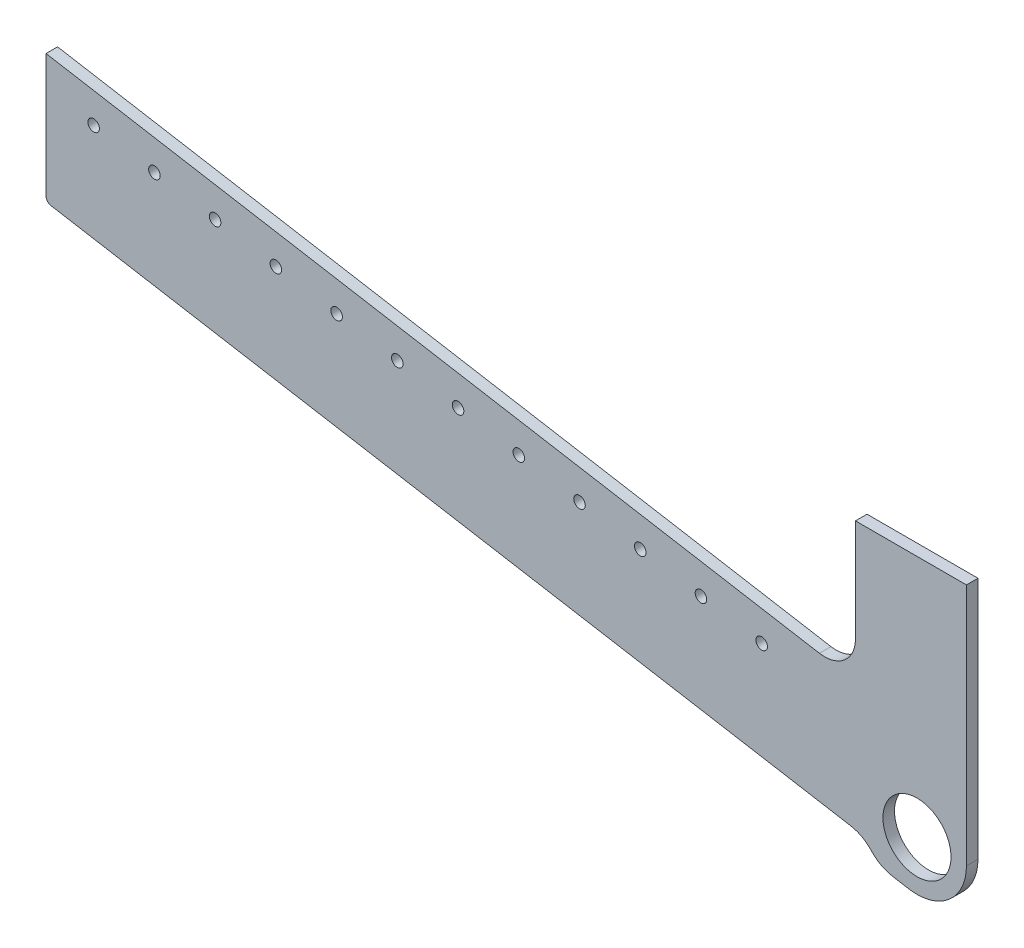
SolidWorks part; units mm, degrees
material "Polypropylene"
ref_plane "Front Plane" through (0, 0, 0) normal (0, 0, 1) x (1, 0, 0)
ref_plane "Top Plane" through (0, 0, 0) normal (0, 1, 0) x (1, 0, 0)
ref_plane "Right Plane" through (0, 0, 0) normal (1, 0, 0) x (0, 0, -1)
sketch "Sketch1" plane through (0, 0, 0) normal (0, 0, 1) x (1, 0, 0)
  line L0 (19.05, 0) -> (19.05, -76.2) construction
  line L1 (0, 19.05) -> (-57.15, 19.05) construction
  line L2 (19.05, -155.575) -> (168.9894, -155.575) construction
  line L3 (0, -95.25) -> (-57.15, -95.25) construction
  line L4 (-57.15, -95.25) -> (-57.15, 19.05) construction
  line L5 (168.9894, 7.239) -> (168.9894, -18.161) construction
  line L6 (168.9894, -18.161) -> (168.9894, -155.575) construction
  line L7 (168.9894, 7.239) -> (143.6189, 6.0141) construction
  line L8 (143.6189, 6.0141) -> (19.05, 0) construction
  line L9 (165.5424, -12.8509) -> (158.8645, -11.7052)
  line L12 (197.5644, 110.4886) -> (197.5644, -33.1911) construction
  line L16 (-190.0553, 107.5461) -> (-190.0553, 56.7461)
  line L17 (-190.0553, 107.5461) -> (128.7712, 52.8423)
  line L23 (-187.9448, 54.2427) -> (141.5847, -2.2975)
  line L24 (143.6189, 65.3594) -> (143.6189, 107.5461)
  line L25 (143.6189, 107.5461) -> (189.3729, 107.5461)
  line L50 (189.3729, 107.5461) -> (189.3729, 7.239)
  arc A0 (19.05, 0) -> (0, 19.05) centre (0, 0) ccw construction
  arc A1 (19.05, -76.2) -> (0, -95.25) centre (0, -76.2) cw construction
  circle A2 centre (168.9894, 7.239) radius 14.0335
  arc A3 (168.9894, -18.161) -> (143.6189, 6.0141) centre (168.9894, 7.239) ccw construction
  arc A4 (165.5424, -12.8509) -> (189.3729, 7.239) centre (168.9894, 7.239) ccw
  circle A15 centre (104.9708, 44.4781) radius 2.3812
  circle A16 centre (79.9366, 48.7734) radius 2.3813
  circle A17 centre (54.9024, 53.0687) radius 2.3812
  circle A18 centre (29.8682, 57.3641) radius 2.3812
  circle A19 centre (4.8341, 61.6594) radius 2.3813
  circle A20 centre (-20.2001, 65.9547) radius 2.3813
  circle A21 centre (-45.2343, 70.2501) radius 2.3813
  circle A22 centre (-70.2685, 74.5454) radius 2.3813
  arc A31 (-187.9448, 54.2427) -> (-190.0553, 56.7461) centre (-187.5153, 56.7461) cw
  arc A34 (158.8645, -11.7052) -> (150.2246, -7.0013) centre (161.4417, 3.3154) cw
  arc A48 (141.5847, -2.2975) -> (150.2246, -7.0013) centre (139.0075, -17.318) cw
  arc A101 (128.7712, 52.8423) -> (143.6189, 65.3594) centre (130.9189, 65.3594) ccw
  circle A102 centre (-170.4052, 91.7267) radius 2.3812
  circle A103 centre (-145.371, 87.4314) radius 2.3812
  circle A104 centre (-120.3368, 83.1361) radius 2.3813
  circle A105 centre (-95.3027, 78.8407) radius 2.3812
  point P51 (-190.0553, 48.162)
  point P92 (143.8191, 3.8303)
  point P95 (150.6057, -10.2881)
  point P107 (-190.0576, 105.312)
  dimension "D1" = 19.05
  dimension "D4" = 19.05
  dimension "D6" = 28.067
  dimension "D7" = 50.8
  dimension "D10" = 6.35
  dimension "D13" = 28.575
  dimension "D26" = 2.54
  dimension "D27" = 15.24
  dimension "D14" = 12.7
  dimension "D2" = 155.575
  dimension "D3" = 76.2
  dimension "D5" = 114.3
  dimension "D8" = 137.414
  dimension "D9" = 124.714
  dimension "D11" = 12.5
  dimension "D12" = 50.8
  dimension "D40" = 17.2798
  dimension "D41" = 9.4076
extrude "Boss-Extrude1" add sketch "Sketch1" along normal blind 4.7625
sketch "Sketch2" plane through (0, 0, 4.7625) normal (0, 0, 1) x (1, 0, 0)
  line L0 (-188.8163, 48.0139) -> (-189.0331, 50.6154)
  line L1 (-189.2853, 50.8905) -> (-190.3098, 51.0663)
  line L2 (-190.6393, 50.891) -> (-191.7109, 48.5105)
  line L3 (-191.7701, 48.4563) -> (-191.7658, 48.4813) construction
  line L4 (-189.7976, 50.9784) -> (-190.2743, 48.1996) construction
  line L5 (-188.7743, 49.2566) -> (-191.3363, 49.6962) construction
  line L6 (158.8645, -11.7052) -> (165.5424, -12.8509) construction
  line L7 (-191.1886, 49.6708) -> (-191.441, 48.1996) construction
  line L8 (-188.922, 49.2819) -> (-189.1077, 48.1996) construction
  line L11 (-188.7786, 47.943) -> (-191.7701, 48.4563)
  line L13 (-188.7743, 47.968) -> (-188.3036, 47.8873)
  line L14 (-188.3036, 47.8873) -> (-188.3079, 47.8622)
  line L15 (-188.3079, 47.8622) -> (-188.7786, 47.943)
  line L16 (-188.7786, 47.943) -> (-188.7743, 47.968) construction
  line L17 (-192.2365, 48.5621) -> (-192.2408, 48.537)
  line L18 (-192.2408, 48.537) -> (-191.7701, 48.4563)
  line L19 (-191.7658, 48.4813) -> (-192.2365, 48.5621)
  line L21 (-190.0553, 107.5461) -> (-190.0553, 56.7461) construction
  arc A0 (-190.3098, 51.0663) -> (-190.6393, 50.891) centre (-190.3613, 50.7659) ccw
  arc A1 (-189.0331, 50.6154) -> (-189.2853, 50.8905) centre (-189.3369, 50.5901) ccw
  arc A2 (-191.7658, 48.4813) -> (-191.7109, 48.5105) centre (-191.7572, 48.5314) ccw
  arc A3 (-188.8163, 48.0139) -> (-188.7743, 47.968) centre (-188.7657, 48.0181) ccw
  point P6 (-190.0553, 49.4764)
  dimension "D1" = 0.0254
  dimension "Root_fillet" = 0.3048
  dimension "Break_rad" = 0.0508
  dimension "Gap_width" = 2.2997
  dimension "Dedendum" = 1.524
  dimension "Addendum_plus" = 1.2954
  dimension "Pressure_angle" = 14.5
  dimension "D2" = 0.4775
sketch "Sketch3" plane through (0, 0, 4.7625) normal (0, 0, 1) x (1, 0, 0)
  line L6 (189.3729, 333.3075) -> (125.8729, 333.3075) construction
  line L7 (189.3729, 333.3075) -> (-153.5271, 333.3075) construction
  line L8 (125.8729, 333.3075) -> (115.9933, 323.428)
  line L9 (107.3751, 320.5539) -> (17.9229, 333.3075)
  line L10 (125.8729, 333.3075) -> (17.9229, 333.3075)
  arc A0 (115.9933, 323.428) -> (107.3751, 320.5539) centre (108.8091, 330.6122) cw
  dimension "D1" = 10.16
extrude "Cut-Extrude1" cut sketch "Sketch3" against normal through all
